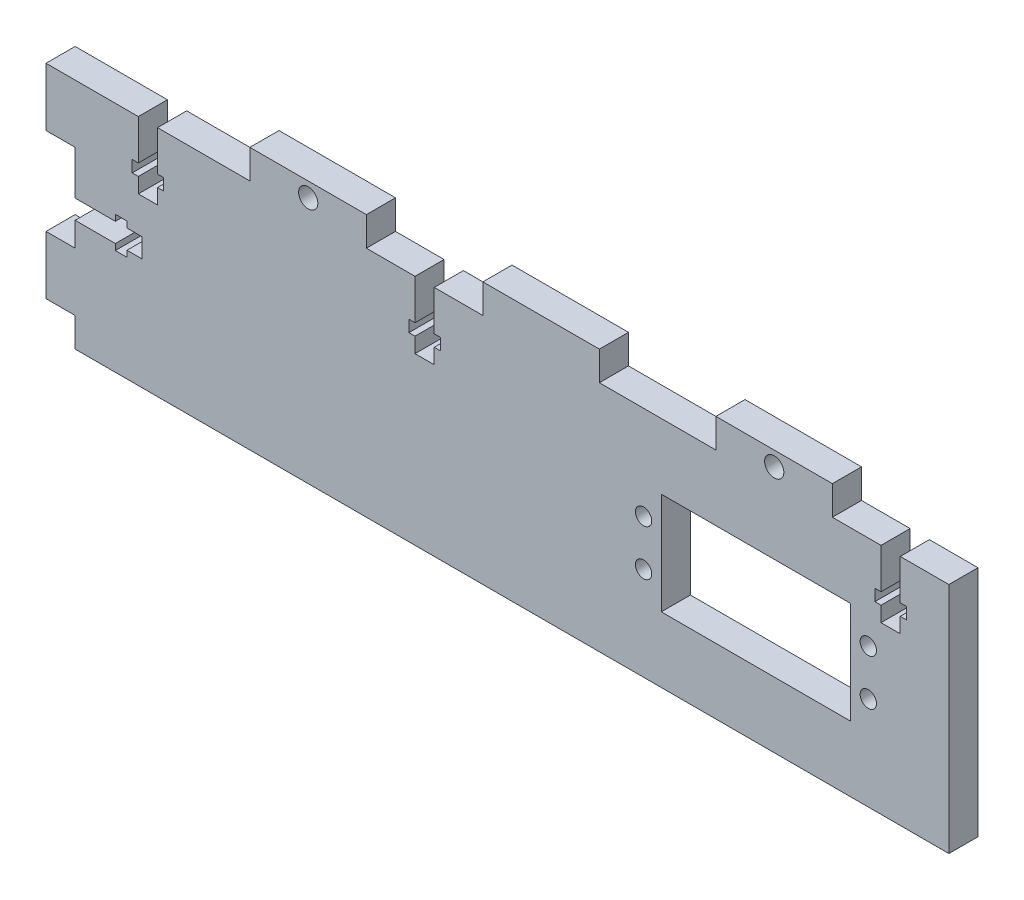
SolidWorks part; units mm, degrees
ref_plane "Front Plane" through (0, 0, 0) normal (0, 0, 1) x (1, 0, 0)
ref_plane "Top Plane" through (0, 0, 0) normal (0, 1, 0) x (1, 0, 0)
ref_plane "Right Plane" through (0, 0, 0) normal (1, 0, 0) x (0, 0, -1)
sketch "Sketch1" plane through (0, 0, 0) normal (0, 0, 1) x (1, 0, 0)
  line L0 (69.2576, 0) -> (-63.1151, 0) construction
  line L1 (42.067, 25.4) -> (-148.433, 25.4)
  line L2 (42.067, 25.4) -> (42.067, -25.4)
  line L3 (42.067, -25.4) -> (-148.433, -25.4)
  line L4 (-148.433, 25.4) -> (-148.433, -25.4)
  line L7 (25.98, 9.3599) -> (20.1295, 9.3599) construction
  line L8 (20.1295, -9.3599) -> (25.98, -9.3599) construction
  line L9 (-148.433, -69.85) -> (-148.433, 49.2353) construction
  line L10 (27.25, 6.27) -> (27.25, 8.0899) construction
  dimension "D1" = 50.8
  dimension "D2" = 14.817
extrude "Boss-Extrude1" add sketch "Sketch1" along normal blind 6.35
sketch "Sketch2" plane through (0, 0, 6.35) normal (0, 0, 1) x (1, 0, 0)
  line L0 (-43.1818, 0) -> (35.1848, 0) construction
  line L1 (-20.6375, 11.1125) -> (20.6375, 11.1125)
  line L2 (-20.6375, 11.1125) -> (-20.6375, -11.1125)
  line L3 (-20.6375, -11.1125) -> (20.6375, -11.1125)
  line L4 (20.6375, 11.1125) -> (20.6375, -11.1125)
  line L5 (-19.6295, 10.033) -> (19.6295, 10.033) construction
  line L6 (19.6295, -10.033) -> (-19.6295, -10.033) construction
  line L7 (0, 18.8234) -> (0, -13.1279) construction
  line L8 (-20.1295, -9.533) -> (-20.1295, 9.533) construction
  line L9 (20.1295, 9.533) -> (20.1295, -9.533) construction
  dimension "D1" = 22.225
  dimension "D2" = 41.275
extrude "Cut-Extrude1" cut sketch "Sketch2" against normal through all
sketch "Sketch3" plane through (0, 25.4, 0) normal (0, 1, 0) x (1, 0, 0)
  line L0 (16.667, 0) -> (16.667, -6.35)
  line L1 (42.067, 0) -> (-148.433, 0) construction
  line L2 (42.067, -6.35) -> (-148.433, -6.35) construction
  line L3 (16.667, -6.35) -> (-8.733, -6.35)
  line L4 (-8.733, -6.35) -> (-8.733, 0)
  line L5 (-8.733, 0) -> (16.667, 0)
  dimension "D1" = 25.4
  dimension "D2" = 25.4
extrude "Boss-Extrude2" add sketch "Sketch3" along normal blind 6.35
pattern_linear "LPattern1" count 3 spacing 50.8 along (-1, 0, 0) of "Boss-Extrude2"
sketch "Sketch4" plane through (-148.433, 0, 0) normal (-1, 0, 0) x (0, 0, 1)
  line L0 (6.35, 25.4) -> (6.35, 12.7)
  line L1 (6.35, 25.4) -> (6.35, -25.4) construction
  line L2 (6.35, 12.7) -> (0, 12.7)
  line L3 (0, 25.4) -> (0, -25.4) construction
  line L4 (0, 12.7) -> (0, 25.4)
  line L5 (0, 25.4) -> (6.35, 25.4)
  dimension "D1" = 12.7
extrude "Boss-Extrude3" add sketch "Sketch4" along normal blind 6.35
pattern_linear "LPattern2" count 2 spacing 31.75 along (0, -1, 0) of "Boss-Extrude3"
sketch "Sketch5" plane through (0, 0, 6.35) normal (0, 0, 1) x (1, 0, 0)
  line L1 (29.367, 25.4) -> (29.367, -8.4837) construction
  line L2 (42.067, 25.4) -> (16.667, 25.4) construction
  line L3 (-72.233, 25.4) -> (-72.233, 3.5007) construction
  line L4 (-59.533, 25.4) -> (-84.933, 25.4) construction
  line L5 (-132.558, 25.4) -> (-132.558, 4.6588) construction
  line L6 (-110.333, 25.4) -> (-154.783, 25.4) construction
  line B0 (31.4625, 25.4) -> (27.2715, 25.4)
  line B1 (27.2715, 14.097) -> (25.938, 14.097)
  line B2 (25.938, 14.097) -> (25.938, 16.637)
  line B3 (25.938, 16.637) -> (27.2715, 16.637)
  line B4 (27.2715, 16.637) -> (27.2715, 25.4)
  line B5 (27.2715, 14.097) -> (27.2715, 10.795)
  line B6 (27.2715, 10.795) -> (31.4625, 10.795)
  line B7 (31.4625, 14.097) -> (31.4625, 10.795)
  line B8 (31.4625, 16.637) -> (31.4625, 25.4)
  line B9 (32.796, 16.637) -> (31.4625, 16.637)
  line B10 (32.796, 14.097) -> (32.796, 16.637)
  line B11 (31.4625, 14.097) -> (32.796, 14.097)
  line B12 (-70.1375, 25.4) -> (-74.3285, 25.4)
  line B13 (-74.3285, 14.097) -> (-75.662, 14.097)
  line B14 (-75.662, 14.097) -> (-75.662, 16.637)
  line B15 (-75.662, 16.637) -> (-74.3285, 16.637)
  line B16 (-74.3285, 16.637) -> (-74.3285, 25.4)
  line B17 (-74.3285, 14.097) -> (-74.3285, 10.795)
  line B18 (-74.3285, 10.795) -> (-70.1375, 10.795)
  line B19 (-70.1375, 14.097) -> (-70.1375, 10.795)
  line B20 (-70.1375, 16.637) -> (-70.1375, 25.4)
  line B21 (-68.804, 16.637) -> (-70.1375, 16.637)
  line B22 (-68.804, 14.097) -> (-68.804, 16.637)
  line B23 (-70.1375, 14.097) -> (-68.804, 14.097)
  line B24 (-72.233, 25.4) -> (-72.233, 10.795) construction
  line B25 (-130.4625, 25.4) -> (-134.6535, 25.4)
  line B26 (-134.6535, 14.097) -> (-135.987, 14.097)
  line B27 (-135.987, 14.097) -> (-135.987, 16.637)
  line B28 (-135.987, 16.637) -> (-134.6535, 16.637)
  line B29 (-134.6535, 16.637) -> (-134.6535, 25.4)
  line B30 (-134.6535, 14.097) -> (-134.6535, 10.795)
  line B31 (-134.6535, 10.795) -> (-130.4625, 10.795)
  line B32 (-130.4625, 14.097) -> (-130.4625, 10.795)
  line B33 (-130.4625, 16.637) -> (-130.4625, 25.4)
  line B34 (-129.129, 16.637) -> (-130.4625, 16.637)
  line B35 (-129.129, 14.097) -> (-129.129, 16.637)
  line B36 (-130.4625, 14.097) -> (-129.129, 14.097)
sketch_block_instance "TSlot-1"
sketch_block "TSlot" parameters "D1"=3.302, "D2"=2.54, "D3"=3.175, "D4"=8.763, "D5"=1.3462
sketch_block_instance "TSlot-4"
sketch_block_instance "TSlot-5"
extrude "Cut-Extrude2" cut sketch "Sketch5" against normal blind 6.35
sketch "Sketch6" plane through (0, 0, 0) normal (0, 0, -1) x (-1, 0, 0)
  line L0 (-1.854, 31.75) -> (-6.1212, 25.4) construction
  line L1 (-16.667, 31.75) -> (8.733, 31.75) construction
  line L2 (-1.854, 31.75) -> (-1.854, 25.4) construction
  line L3 (-6.1212, 31.75) -> (-1.854, 25.4) construction
  line L4 (-6.1212, 25.4) -> (-6.1212, 31.75) construction
  line L5 (99.746, 31.75) -> (95.4788, 25.4) construction
  line L6 (84.933, 31.75) -> (110.333, 31.75) construction
  line L7 (99.746, 31.75) -> (99.746, 25.4) construction
  line L8 (95.4788, 31.75) -> (99.746, 25.4) construction
  line L9 (95.4788, 25.4) -> (95.4788, 31.75) construction
  circle A0 centre (-3.9876, 28.575) radius 2.0955
  circle A1 centre (97.6124, 28.575) radius 2.0955
  dimension "D1" = 4.191
extrude "Cut-Extrude3" cut sketch "Sketch6" against normal through all
sketch "Sketch7" plane through (0, 0, 6.35) normal (0, 0, 1) x (1, 0, 0)
  line L1 (-148.433, 12.7) -> (-148.433, -6.35) construction
  line L3 (-134.6535, 10.795) -> (-130.4625, 10.795) construction
  line B0 (-148.433, 3.1115) -> (-148.433, -1.0795)
  line B1 (-137.13, -1.0795) -> (-137.13, -2.413)
  line B2 (-137.13, -2.413) -> (-139.67, -2.413)
  line B3 (-139.67, -2.413) -> (-139.67, -1.0795)
  line B4 (-139.67, -1.0795) -> (-148.433, -1.0795)
  line B5 (-137.13, -1.0795) -> (-133.828, -1.0795)
  line B6 (-133.828, -1.0795) -> (-133.828, 3.1115)
  line B7 (-137.13, 3.1115) -> (-133.828, 3.1115)
  line B8 (-139.67, 3.1115) -> (-148.433, 3.1115)
  line B9 (-139.67, 4.445) -> (-139.67, 3.1115)
  line B10 (-137.13, 4.445) -> (-139.67, 4.445)
  line B11 (-137.13, 3.1115) -> (-137.13, 4.445)
  line B12 (-148.433, 1.016) -> (-133.828, 1.016) construction
  dimension "D1" = 6.35
sketch_block_instance "TSlot-6"
extrude "Cut-Extrude4" cut sketch "Sketch7" against normal through all
sketch "Sketch8" plane through (0, 0, 0) normal (0, 0, -1) x (-1, 0, 0)
  circle A0 centre (24.5, -5) radius 1.778
  circle A1 centre (24.5, 5) radius 1.778
  circle A2 centre (-24.5, 5) radius 1.778
  circle A3 centre (-24.5, -5) radius 1.778
extrude "Cut-Extrude5" cut sketch "Sketch8" against normal through all
